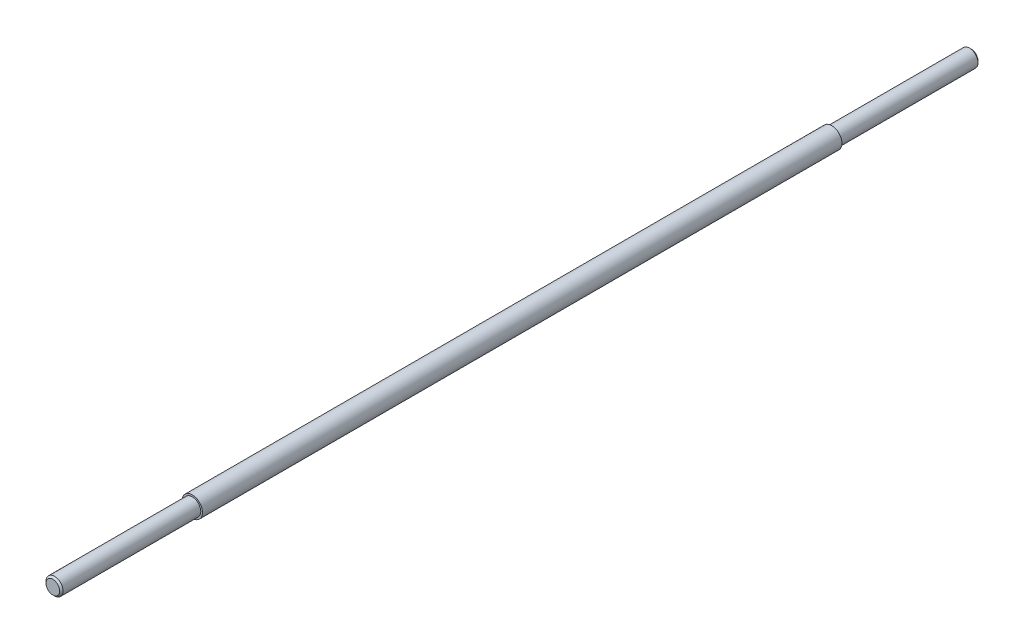
SolidWorks part; units mm, degrees
ref_plane "前视基准面" through (0, 0, 0) normal (0, 0, 1) x (1, 0, 0)
ref_plane "上视基准面" through (0, 0, 0) normal (0, 1, 0) x (1, 0, 0)
ref_plane "右视基准面" through (0, 0, 0) normal (1, 0, 0) x (0, 0, -1)
sketch "草图1" plane through (0, 0, 0) normal (0, 0, 1) x (1, 0, 0)
  circle A0 centre (-7.8162, 3.1672) radius 3
  dimension "D1" = 6
extrude "凸台-拉伸1" add sketch "草图1" along normal blind 188
sketch "草图2" plane through (0, 0, 0) normal (0, 0, -1) x (-1, 0, 0)
  circle A0 centre (7.8162, 3.1672) radius 2.5
  dimension "D1" = 5
extrude "凸台-拉伸2" add sketch "草图2" along normal blind 41
sketch "草图3" plane through (0, 0, 188) normal (0, 0, 1) x (1, 0, 0)
  circle A0 centre (-7.8162, 3.1672) radius 2.5
  dimension "D1" = 5
extrude "凸台-拉伸3" add sketch "草图3" along normal blind 41
chamfer "倒角1" distance 0.5 angle 45 2 edges at (-10.3162, 3.1672, -41) (-5.3162, 3.1672, 229)
